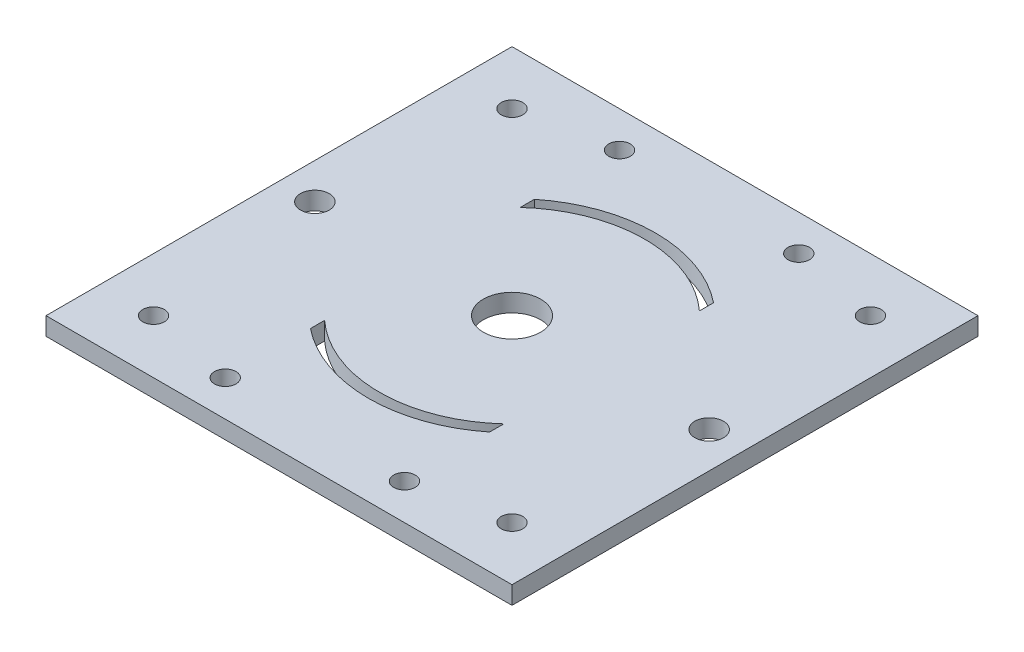
SolidWorks part; units mm, degrees
ref_plane "Front Plane" through (0, 0, 0) normal (0, 0, 1) x (1, 0, 0)
ref_plane "Top Plane" through (0, 0, 0) normal (0, 1, 0) x (1, 0, 0)
ref_plane "Right Plane" through (0, 0, 0) normal (1, 0, 0) x (0, 0, -1)
sketch "Sketch1" plane through (0, 0, 0) normal (0, 1, 0) x (1, 0, 0)
  line L0 (0, 65) -> (0, -65) construction
  line L1 (-65, 65) -> (65, 65)
  line L2 (-65, 65) -> (-65, -65)
  line L3 (-65, -65) -> (65, -65)
  line L4 (65, 65) -> (65, -65)
  line L5 (-65, 65) -> (65, -65) construction
  line L6 (-65, -65) -> (65, 65) construction
  line L7 (-65, 0) -> (65, 0) construction
  circle A0 centre (-50, 50) radius 3
  circle A1 centre (50, 50) radius 3
  circle A2 centre (50, -50) radius 3
  circle A3 centre (-50, -50) radius 3
  point P0 (0, 0)
  dimension "D3" = 6
  dimension "D1" = 130
  dimension "D2" = 130
  dimension "D4" = 50
  dimension "D5" = 50
extrude "Boss-Extrude1" add sketch "Sketch1" along normal blind 5
sketch "Sketch2" plane through (0, 5, 0) normal (0, 1, 0) x (1, 0, 0)
  circle A0 centre (0, 0) radius 8
  dimension "D1" = 16
extrude "Cut-Extrude1" cut sketch "Sketch2" against normal up to surface (5 mm away) up to face at (0, 0, 0)
sketch "Sketch3" plane through (0, 5, 0) normal (0, 1, 0) x (1, 0, 0)
  line L0 (0, 8) -> (0, -8) construction
  circle A0 centre (-55, 0) radius 4
  circle A1 centre (0, 0) radius 8 construction
  circle A2 centre (55, 0) radius 4
  dimension "D1" = 8
  dimension "D2" = 55
extrude "Cut-Extrude2" cut sketch "Sketch3" against normal up to surface (5 mm away) up to face at (0, 0, 8)
sketch "Sketch4" plane through (0, 5, 0) normal (0, 1, 0) x (1, 0, 0)
  line L1 (65, 65) -> (-65, 65) construction
  circle A0 centre (-25, 55) radius 3
  circle A1 centre (25, 55) radius 3
  circle A2 centre (-25, -55) radius 3
  circle A3 centre (25, -55) radius 3
  dimension "D1" = 6
  dimension "D2" = 10
  dimension "D3" = 50
extrude "Cut-Extrude3" cut sketch "Sketch4" against normal blind 10
sketch "Sketch5" plane through (0, 5, 0) normal (0, 1, 0) x (1, 0, 0)
  line L0 (25, 31.225) -> (25, 27.2764)
  line L1 (-25, 31.225) -> (-25, 27.2764)
  line L2 (25, -27.2764) -> (25, -31.225)
  line L3 (-25, -27.2764) -> (-25, -31.225)
  arc A0 (-25, -31.225) -> (25, -31.225) centre (0, 0) ccw
  arc A1 (-25, -27.2764) -> (25, -27.2764) centre (0, 0) ccw
  circle A2 centre (0, 0) radius 40 construction
  circle A3 centre (0, 0) radius 37 construction
  arc A4 (25, 31.225) -> (-25, 31.225) centre (0, 0) ccw
  arc A5 (25, 27.2764) -> (-25, 27.2764) centre (0, 0) ccw
  dimension "D1" = 80
  dimension "D3" = 25
  dimension "D4" = 25
  dimension "D2" = 3
extrude "Cut-Extrude4" cut sketch "Sketch5" against normal blind 10
